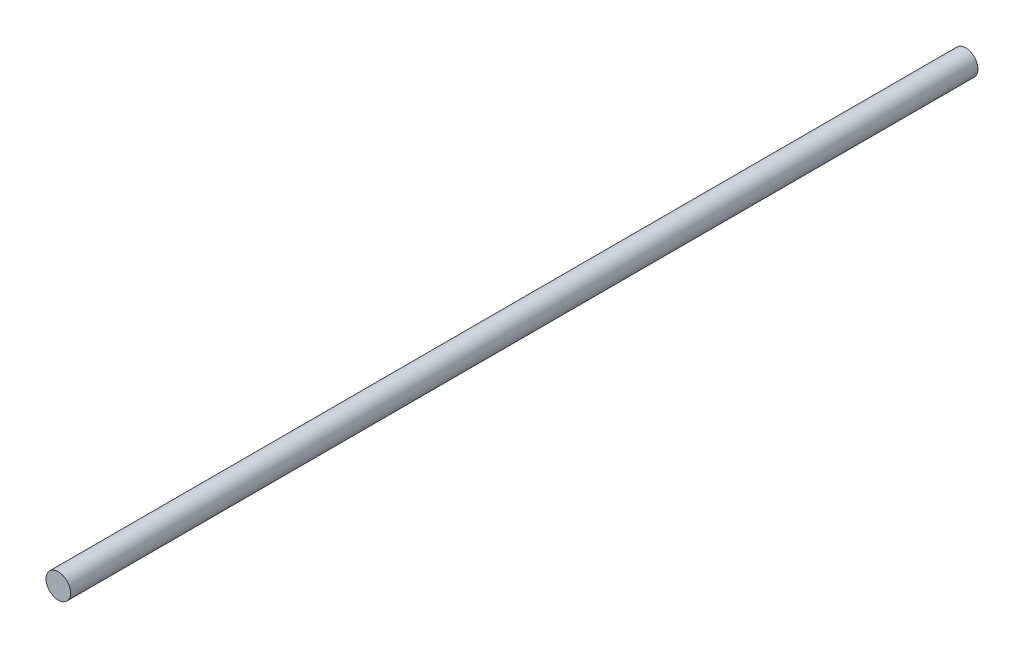
SolidWorks part; units mm, degrees
ref_plane "Plan de face" through (0, 0, 0) normal (0, 0, 1) x (1, 0, 0)
ref_plane "Plan de dessus" through (0, 0, 0) normal (0, 1, 0) x (1, 0, 0)
ref_plane "Plan de droite" through (0, 0, 0) normal (1, 0, 0) x (0, 0, -1)
sketch "Esquisse1" plane through (0, 0, 0) normal (0, 0, 1) x (1, 0, 0)
  circle A0 centre (0, 0) radius 2.105
  dimension "D1" = 4.21
extrude "Boss.-Extru.1" add sketch "Esquisse1" along normal blind 155 contours A0
